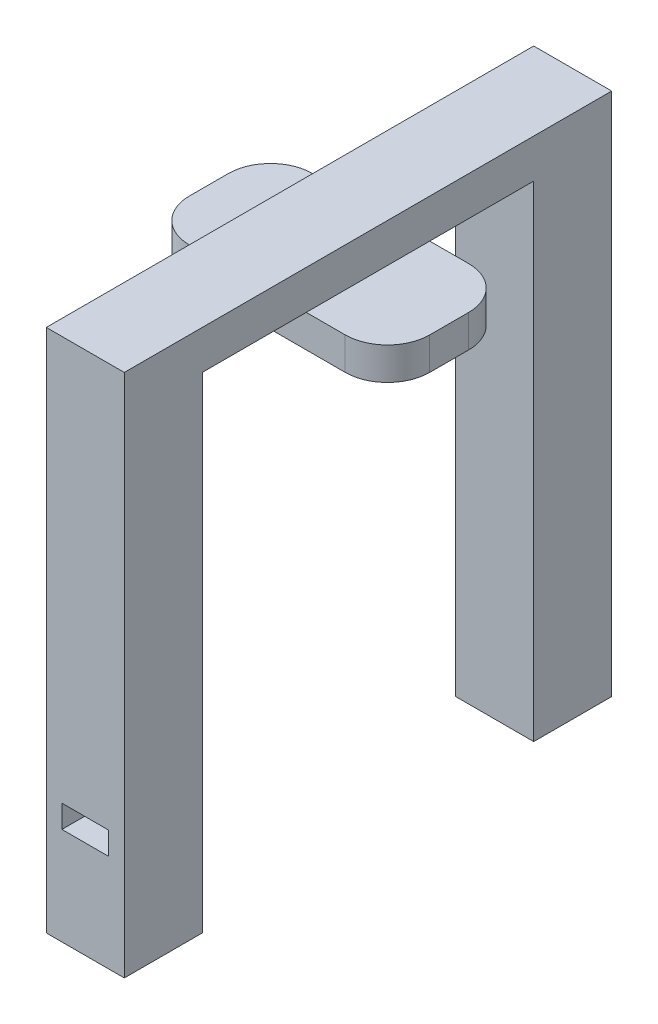
SolidWorks part; units mm, degrees
ref_plane "Plan de face" through (0, 0, 0) normal (0, 0, 1) x (1, 0, 0)
ref_plane "Plan de dessus" through (0, 0, 0) normal (0, 1, 0) x (1, 0, 0)
ref_plane "Plan de droite" through (0, 0, 0) normal (1, 0, 0) x (0, 0, -1)
sketch "Esquisse1" plane through (0, 0, 0) normal (0, 1, 0) x (1, 0, 0)
  line L1 (-23.3674, 11.4324) -> (13.6326, 11.4324)
  line L2 (-23.3674, 11.4324) -> (-23.3674, -7.5676)
  line L3 (-23.3674, -7.5676) -> (13.6326, -7.5676)
  line L4 (13.6326, 11.4324) -> (13.6326, -7.5676)
  dimension "D1" = 37
  dimension "D2" = 19
extrude "Boss.-Extru.1" add sketch "Esquisse1" along normal blind 5
fillet "Congé1" radius 6.5 4 edges at (-23.3674, 2.5, -11.4324) (13.6326, 2.5, -11.4324) (13.6326, 2.5, 7.5676) (-23.3674, 2.5, 7.5676)
sketch "Esquisse4" plane through (0, 5, 0) normal (0, 1, 0) x (1, 0, 0)
  line L0 (-16.8674, -7.5676) -> (7.1326, -7.5676) construction
  line L1 (-10.8674, -35.5676) -> (1.1326, -35.5676)
  line L2 (-10.8674, -35.5676) -> (-10.8674, 39.4324)
  line L3 (-10.8674, 39.4324) -> (1.1326, 39.4324)
  line L4 (1.1326, -35.5676) -> (1.1326, 39.4324)
  line L5 (13.6326, -1.0676) -> (13.6326, 4.9324) construction
  dimension "D1" = 75
  dimension "D2" = 28
  dimension "D3" = 12
  dimension "D4" = 12.5
extrude "Boss.-Extru.2" add sketch "Esquisse4" along normal blind 6 contours L2 L3 L4 L1
sketch "Esquisse5" plane through (0, 5, 0) normal (0, -1, 0) x (-1, 0, 0)
  line L0 (10.8674, 11.4324) -> (10.8674, 39.4324) construction
  line L1 (-1.1326, 39.4324) -> (10.8674, 39.4324)
  line L2 (-1.1326, 39.4324) -> (-1.1326, 27.4324)
  line L3 (-1.1326, 27.4324) -> (10.8674, 27.4324)
  line L4 (10.8674, 39.4324) -> (10.8674, 27.4324)
  line L5 (10.8674, -35.5676) -> (10.8674, -7.5676) construction
  line L6 (-1.1326, -35.5676) -> (10.8674, -35.5676)
  line L7 (-1.1326, -35.5676) -> (-1.1326, -23.5676)
  line L8 (-1.1326, -23.5676) -> (10.8674, -23.5676)
  line L9 (10.8674, -35.5676) -> (10.8674, -23.5676)
  line M1 (-1.1326, 39.4324) -> (-1.1326, 11.4324)
  line M3 (10.8674, 11.4324) -> (10.8674, 39.4324)
  line M4 (10.8674, 39.4324) -> (-1.1326, 39.4324)
  dimension "D1" = 12
  dimension "D2" = 12
extrude "Boss.-Extru.3" add sketch "Esquisse5" along normal blind 74.7 contours L3 M1 M3 M4 | L8 L9 L6 L7
sketch "Esquisse6" plane through (0, -69.7, 0) normal (0, -1, 0) x (1, 0, 0)
  line L0 (1.1326, 35.5676) -> (1.1326, 23.5676) construction
  line L2 (1.1326, 35.5676) -> (-10.8674, 35.5676) construction
  line L3 (1.1326, -39.4324) -> (1.1326, -27.4324) construction
  line L4 (1.1326, -27.4324) -> (-10.8674, -27.4324) construction
  circle A0 centre (-4.8674, 29.5676) radius 2.075
  circle A1 centre (-4.8674, -33.4324) radius 2.075
  dimension "D1" = 4.15
  dimension "D2" = 4.15
  dimension "D3" = 6
  dimension "D4" = 6
  dimension "D5" = 6
  dimension "D6" = 6
extrude "Enlèv. mat.-Extru.1" cut sketch "Esquisse6" against normal blind 40 contours A0 | A1
sketch "Esquisse7" plane through (0, 0, 35.5676) normal (0, 0, 1) x (1, 0, 0)
  line L0 (1.1326, -69.7) -> (-10.8674, -69.7) construction
  line L1 (-1.2674, -54.7) -> (-8.4674, -54.7)
  line L2 (-1.2674, -54.7) -> (-1.2674, -51.2)
  line L3 (-1.2674, -51.2) -> (-8.4674, -51.2)
  line L4 (-8.4674, -54.7) -> (-8.4674, -51.2)
  line L5 (-10.8674, 11) -> (-10.8674, -69.7) construction
  point P8 (-3.8092, -58.8384)
  dimension "D1" = 15
  dimension "D2" = 7.2
  dimension "D3" = 2.4
  dimension "D4" = 3.5
extrude "Enlèv. mat.-Extru.2" cut sketch "Esquisse7" against normal blind 10.25 contours L1 L4 L3 L2
sketch "Esquisse8" plane through (0, 0, -39.4324) normal (0, 0, -1) x (-1, 0, 0)
  line L0 (10.8674, -69.7) -> (-1.1326, -69.7) construction
  line L1 (8.4674, -54.7) -> (1.2674, -54.7)
  line L2 (8.4674, -54.7) -> (8.4674, -51.2)
  line L3 (8.4674, -51.2) -> (1.2674, -51.2)
  line L4 (1.2674, -54.7) -> (1.2674, -51.2)
  line L5 (10.8674, 11) -> (10.8674, -69.7) construction
  dimension "D1" = 15
  dimension "D2" = 3.5
  dimension "D3" = 7.2
  dimension "D4" = 2.4
extrude "Enlèv. mat.-Extru.3" cut sketch "Esquisse8" against normal blind 10.25 contours L1 L4 L3 L2
equation "\"c1@Esquisse2\" = 20"
equation "\"D2@Esquisse4\"=(75-19)/2"
equation "\"D4@Esquisse4\"=(37-12)/2"
equation "\"D1@Boss.-Extru.3\"=58+16.7"
equation "\"D3@Esquisse7\"=(12-7.2)/2"
